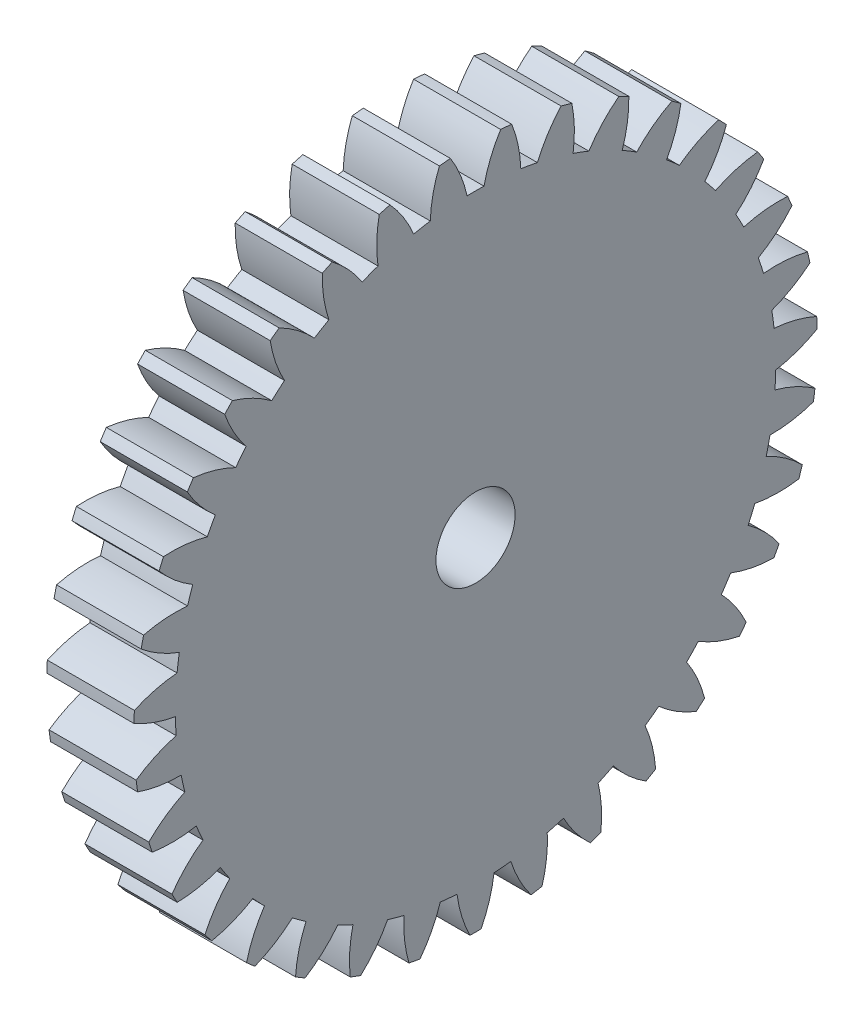
SolidWorks part; units mm, degrees
ref_plane "Plane1" through (0, 0, 0) normal (0, 0, 1) x (1, 0, 0)
ref_plane "Plane2" through (0, 0, 0) normal (0, 1, 0) x (1, 0, 0)
ref_plane "Plane3" through (0, 0, 0) normal (1, 0, 0) x (0, 0, -1)
sketch "HoldingSke" plane through (0, 0, 0) normal (0, 1, 0) x (1, 0, 0)
  line L0 (0, 0) -> (1.1702, -0.8194)
  line L1 (-15, 0) -> (100, 0) construction
  line L2 (0, 0) -> (-2.1039, 2.3779)
  line L3 (0, 0) -> (-11.863, 4.5341)
  line L4 (0, 0) -> (7.0742, 4.9534)
  line L5 (0, 0) -> (-46.8476, -17.4728)
  line L6 (0, 0) -> (-2.7356, -1.8457)
  line L7 (-2.1039, 2.3779) -> (8.6586, 51.2059)
  line L8 (-76.2, 54.61) -> (-75.7, 54.61)
  line L9 (-71.009, 38.7566) -> (-53.1078, 45.2721)
  line L10 (-76.2, 71.12) -> (104.1128, 71.12)
  line L11 (0, 0) -> (-3.3, 0)
  line L12 (-76.2, 101.6) -> (-76.173, 101.6)
  line L13 (24.9733, 27.94) -> (52.9518, 28.4284)
  line L14 (24.9733, 27.94) -> (24.9743, 27.94)
  line L15 (24.9733, 27.94) -> (100.4006, 29.5858)
  line L16 (-63.627, -0.7) -> (-12.827, -0.7)
  circle A0 centre (0, 0) radius 1.5
  circle A1 centre (0, 0) radius 11.374
  circle A2 centre (0, 0) radius 37.5
  circle A3 centre (0, 0) radius 1.5
  dimension "MHD" = 22.748
  dimension "Hub_dia" = 75
  dimension "Bore" = 3
  dimension "MBD" = 3
  dimension "Num_teeth" = 35
  dimension "Pitch" = 1.4286
  dimension "Overall_len" = 50
  dimension "Show_teeth" = 35
  dimension "Thickness" = 3.3
  dimension "OAL" = 50.0001
  dimension "T_dim" = 0.5
  dimension "Ap" = 20
  dimension "H" = 19.05
  dimension "Pitch_radius" = 180.3128
  dimension "Width" = 3.3
  dimension "Backlash" = 0.027
  dimension "Addendum_fac" = 1
  dimension "Dedendum_fac" = 1.25
  dimension "Clearance_fac" = 0.25
  dimension "Dedendum_add" = 0.001
  dimension "Module" = 0.7
sketch "BasProSke" plane through (0, 0, 0) normal (0, 1, 0) x (1, 0, 0)
  line L0 (-10, 0) -> (60, 0) construction
  line L1 (0, 0) -> (0, 12.95)
  line L2 (0, 0) -> (3.3, 0)
  line L3 (3.3, 0) -> (3.3, 12.95)
  line L4 (3.3, 12.95) -> (0, 12.95)
  dimension "Thickness" = 3.3
  dimension "Diameter" = 25.9
revolve "Base-Revolve" add sketch "BasProSke" angle 360 about L0
sketch "TooCutSke" plane through (0, 0, 0) normal (1, 0, 0) x (0, 0, -1)
  line L1 (0, 0) -> (0, 107) construction
  line L2 (0, 0) -> (-0.5968, 12.2355) construction
  line L3 (0, 0) -> (-2.1943, 24.3808) construction
  line L4 (-0.5968, 12.2355) -> (-1.0972, 12.1904) construction
  arc A0 (0.32, 11.3695) -> (-0.32, 11.3695) centre (0, 0) ccw
  arc A1 (0.9664, 12.9394) -> (-0.9664, 12.9394) centre (0, 0) ccw
  circle A2 centre (0, 0) radius 12.25 construction
  circle A3 centre (0, 0) radius 11.5112 construction
  arc A4 (-0.32, 11.3695) -> (-0.9664, 12.9394) centre (-5.1057, 10.317) ccw
  arc A5 (0.9664, 12.9394) -> (0.32, 11.3695) centre (5.1057, 10.317) ccw
  dimension "Root_dia" = 22.748
  dimension "Overcut_dia" = 25.9508
  dimension "Pitch_dia" = 24.5
  dimension "Base_dia" = 23.0225
  dimension "Flank_rad" = 4.9
  dimension "Half_ang" = 5.143
  dimension "Half_CT" = 0.5023
extrude "ToothCut" cut sketch "TooCutSke" along normal through all
fillet "Breaks" [suppressed] radius 0.014
fillet "RootFillets" [suppressed] radius 0.176
pattern_circular "TeethCuts" count 35 every 10.286 about axis through (-10, 0, 0) along (1, 0, 0) of "ToothCut", "RootFillets", "Breaks"
sketch "HubNeaOneSke" plane through (0, 0, 0) normal (-1, 0, 0) x (0, 0, 1)
  circle A0 centre (0, 0) radius 11.374
  dimension "Diameter" = 22.748
extrude "HubNearOne" [suppressed] add sketch "HubNeaOneSke" along normal blind 46.7001
sketch "HubNeaBotSke" plane through (0, 0, 0) normal (-1, 0, 0) x (0, 0, 1)
  circle A0 centre (0, 0) radius 11.374
  dimension "Diameter" = 22.748
extrude "HubNearBoth" [suppressed] add sketch "HubNeaBotSke" along normal blind 23.35
ref_plane "FarPln" through (3.3, 0, 0) normal (1, 0, 0) x (0, 0, -1)
sketch "HubFarSke" plane through (3.3, 0, 0) normal (1, 0, 0) x (0, 0, -1)
  circle A0 centre (0, 0) radius 11.374
  dimension "Diameter" = 22.748
extrude "HubFar" [suppressed] add sketch "HubFarSke" along normal blind 23.35
sketch "BorSke" plane through (0, 0, 0) normal (1, 0, 0) x (0, 0, -1)
  circle A0 centre (0, 0) radius 1.5
  dimension "Diameter" = 3
extrude "Bore" cut sketch "BorSke" along normal mid plane 100.0001
sketch "KeySke" plane through (0, 0, 0) normal (1, 0, 0) x (0, 0, -1)
  line L0 (-0.6, 0) -> (-0.6, 2)
  line L1 (-0.6, 2) -> (0.6, 2)
  line L2 (0.6, 2) -> (0.6, 0)
  line L3 (0, 0) -> (0, 34) construction
  line L4 (-0.6, 0) -> (0.6, 0)
  dimension "Offset" = 2
  dimension "Width" = 1.2
extrude "Keyway" [suppressed] cut sketch "KeySke" along normal mid plane 100.0001
pattern_circular "Keyway2" [suppressed] count 2 every 90 about axis through (-10, 0, 0) along (1, 0, 0)
equation "' \"Module@HoldingSke\" = 6.35"
equation "' \"Num_teeth@HoldingSke\" = 12"
equation "' \"Ap@HoldingSke\" =  20"
equation "' \"Ap@HoldingSke\" = 20"
equation "' \"Width@HoldingSke\" = 0.5 * 25.4"
equation "' \"Hub_dia@HoldingSke\"= 1 * 25.4"
equation "' \"Hub_dia@HoldingSke\" = 1 * 25.4"
equation "' \"Overall_len@HoldingSke\" = 1.0 * 25.4"
equation "' \"Bore@HoldingSke\" = 0.75 * 25.4"
equation "' \"T_dim@HoldingSke\" = 0.1 * 25.4"
equation "' \"Width@KeySke\" = 0.25 * 25.4"
equation "' \"Show_teeth@HoldingSke\" = 13"
equation "' \"Backlash@HoldingSke\" = 0.009 * 25.4"
equation "' \"Addendum_fac@HoldingSke\" = 1.0"
equation "' \"Dedendum_fac@HoldingSke\" = 1.25"
equation "' \"Dedendum_add@HoldingSke\" = 0.00005 * 25.4"
equation "' \"Clearance_fac@HoldingSke\" = 0.25"
equation "\"Pitch@HoldingSke\" = 1 / \"Module@HoldingSke\""
equation "\"Overcut_dia@TooCutSke\" = (\"Num_teeth@HoldingSke\" + 2 * \"Addendum_fac@HoldingSke\") / \"Pitch@HoldingSke\" + 0.002 * 25.4"
equation "\"Pitch_dia@TooCutSke\" = \"Num_teeth@HoldingSke\" / \"Pitch@HoldingSke\""
equation "\"Base_dia@TooCutSke\" = \"Num_teeth@HoldingSke\" / \"Pitch@HoldingSke\" * cos((\"Ap@HoldingSke\"  * 3.14159265 / 180))"
equation "\"Root_dia@TooCutSke\" = (\"Num_teeth@HoldingSke\" + 2) / \"Pitch@HoldingSke\" - 2 * (\"Addendum_fac@HoldingSke\" + \"Dedendum_fac@HoldingSke\") / \"Pitch@HoldingSke\" - \"Dedendum_add@HoldingSke\" * 2"
equation "\"Half_ang@TooCutSke\" = 180 / \"Num_teeth@HoldingSke\""
equation "\"Half_CT@TooCutSke\" = \"Num_teeth@HoldingSke\" / \"Pitch@HoldingSke\" * sin((3.14159265 / 2 / \"Num_teeth@HoldingSke\")) / 2 - 7 * \"Backlash@HoldingSke\" / 4"
equation "\"Flank_rad@TooCutSke\" = \"Num_teeth@HoldingSke\" / \"Pitch@HoldingSke\" / 5"
equation "\"Radius@RootFillets\" = \"Clearance_fac@HoldingSke\" / \"Pitch@HoldingSke\" + \"Dedendum_add@HoldingSke\""
equation "\"Break_rad@Breaks\" = 0.02 / \"Pitch@HoldingSke\""
equation "\"Thickness@HoldingSke\" = \"Width@HoldingSke\""
equation "\"OAL@HoldingSke\" = \"Thickness@HoldingSke\""
equation "\"MHD@HoldingSke\" = (\"Num_teeth@HoldingSke\" + 2) / \"Pitch@HoldingSke\" - 2 * (\"Addendum_fac@HoldingSke\" + \"Dedendum_fac@HoldingSke\")  / \"Pitch@HoldingSke\" - \"Dedendum_add@HoldingSke\" * 2"
equation "\"MBD@HoldingSke\" = (\"Num_teeth@HoldingSke\" + 2) / \"Pitch@HoldingSke\" - 2 * (\"Addendum_fac@HoldingSke\" + \"Dedendum_fac@HoldingSke\")  / \"Pitch@HoldingSke\" - \"Dedendum_add@HoldingSke\" * 2 - 0.002 * 25.4"
equation "\"MHD@HoldingSke\" = ((sgn( \"MHD@HoldingSke\" - \"Hub_dia@HoldingSke\" )-1)*( \"MHD@HoldingSke\" - \"Hub_dia@HoldingSke\" ))/-2+ \"Hub_dia@HoldingSke\""
equation "\"MBD@HoldingSke\" = ((sgn( \"MBD@HoldingSke\" - \"Bore@HoldingSke\" )-1)*( \"MBD@HoldingSke\" - \"Bore@HoldingSke\" ))/-2+ \"Bore@HoldingSke\""
equation "\"OAL@HoldingSke\" = ((sgn( \"OAL@HoldingSke\" - \"Overall_len@HoldingSke\" )+1)*( \"OAL@HoldingSke\" - \"Overall_len@HoldingSke\" ))/2 + \"Overall_len@HoldingSke\" + 0.000002 * 25.4"
equation "\"Num_teeth@TeethCuts\" = int( \"Show_teeth@HoldingSke\" ) + 1"
equation "\"Num_teeth@TeethCuts\" = ((sgn( \"Num_teeth@TeethCuts\" - \"Num_teeth@HoldingSke\" )-1)*( \"Num_teeth@TeethCuts\" - \"Num_teeth@HoldingSke\" ))/-2+ \"Num_teeth@HoldingSke\""
equation "\"Num_teeth@TeethCuts\" = ((sgn( \"Num_teeth@TeethCuts\" - 2.0)+1)*( \"Num_teeth@TeethCuts\" - 2.0))/2 +2.0"
equation "\"Angle@TeethCuts\" = 360.0 / \"Num_teeth@HoldingSke\""
equation "\"Diameter@BasProSke\" = (\"Num_teeth@HoldingSke\" + 2 * \"Addendum_fac@HoldingSke\") / \"Pitch@HoldingSke\""
equation "\"Thickness@BasProSke\"  = \"Thickness@HoldingSke\""
equation "' \"Fillet_rad@BasProSke\" =  \"Thickness@HoldingSke\" * 0.05"
equation "' \"Fillet_rad@BasProSke\" = \"Thickness@HoldingSke\" * 0.05"
equation "\"MHD@HoldingSke\" = ((sgn( \"MHD@HoldingSke\" - \"Root_dia@TooCutSke\" )-1)*( \"MHD@HoldingSke\" - \"Root_dia@TooCutSke\" ))/-2+ \"Root_dia@TooCutSke\""
equation "\"Diameter@HubNeaOneSke\" = \"MHD@HoldingSke\""
equation "\"Length@HubNearOne\" = \"OAL@HoldingSke\" - \"Thickness@BasProSke\""
equation "\"Diameter@HubNeaBotSke\" = \"MHD@HoldingSke\""
equation "\"Length@HubNearBoth\" = ( \"OAL@HoldingSke\" - \"Thickness@BasProSke\" ) / 2.0"
equation "\"Thickness@FarPln\" = \"Thickness@BasProSke\""
equation "\"Diameter@HubFarSke\" = \"MHD@HoldingSke\""
equation "\"Length@HubFar\" = ( \"OAL@HoldingSke\" - \"Thickness@BasProSke\" ) / 2.0"
equation "\"Diameter@BorSke\" = \"MBD@HoldingSke\""
equation "\"D1@Bore\" = \"OAL@HoldingSke\" * 2.0"
equation "\"D1@Keyway\" = \"OAL@HoldingSke\" * 2.0"
equation "\"Offset@KeySke\" = \"T_dim@HoldingSke\" + \"MBD@HoldingSke\" / 2.0"
